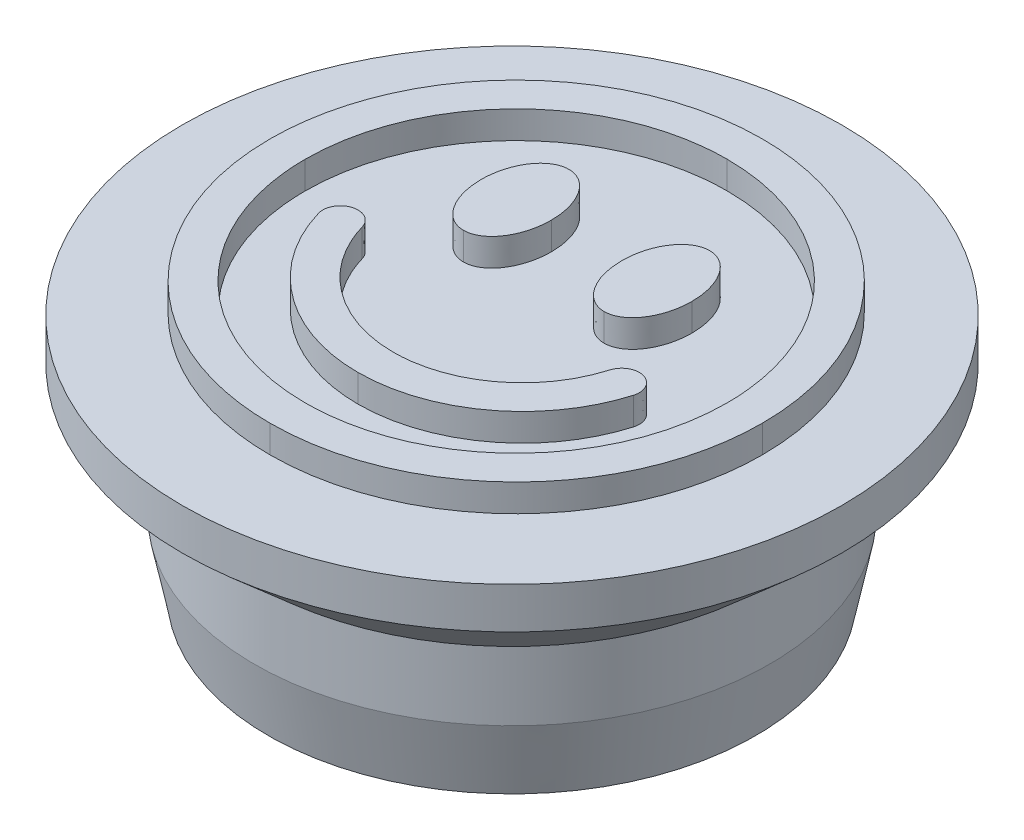
SolidWorks part; units mm, degrees
ref_plane "Front Plane" through (0, 0, 0) normal (0, 0, 1) x (1, 0, 0)
ref_plane "Top Plane" through (0, 0, 0) normal (0, 1, 0) x (1, 0, 0)
ref_plane "Right Plane" through (0, 0, 0) normal (1, 0, 0) x (0, 0, -1)
sketch "Sketch2" plane through (0, 0, 0) normal (0, 0, 1) x (1, 0, 0)
  line L0 (0, 0) -> (18.75, 0)
  line L1 (18.75, 0) -> (18.75, 10)
  line L2 (18.75, 10) -> (24, 14.6301)
  line L3 (24, 14.6301) -> (24, 17.6301)
  line L4 (24, 17.6301) -> (0, 17.6301)
  line L5 (0, 17.6301) -> (0, 0)
  dimension "D1" = 18.75
  dimension "D2" = 10
  dimension "D3" = 3
  dimension "D4" = 24
  dimension "D5" = 7
revolve "Revolve1" add sketch "Sketch2" angle 360 about L5
sketch "Sketch3" plane through (0, 17.6301, 0) normal (0, 1, 0) x (1, 0, 0)
  spline S0 degree 3 poles (0, 15.6649) (8.47, 15.6649) (15.36, 8.7749) (15.36, 0.3049) knots 0 0 0 0 1 1 1 1
  spline S1 degree 3 poles (15.36, 0.3049) (15.36, -8.1651) (8.47, -15.0551) (0, -15.0551) knots 0 0 0 0 1 1 1 1
  spline S2 degree 3 poles (0, -15.0551) (-8.47, -15.0551) (-15.36, -8.1651) (-15.36, 0.3049) knots 0 0 0 0 1 1 1 1
  spline S3 degree 3 poles (-15.36, 0.3049) (-15.36, 8.7749) (-8.47, 15.6649) (0, 15.6649) knots 0 0 0 0 1 1 1 1
  spline S4 degree 3 poles (0, 18.2249) (-9.8975, 18.2249) (-17.92, 10.2024) (-17.92, 0.3049) knots 0 0 0 0 1 1 1 1
  spline S5 degree 3 poles (-17.92, 0.3049) (-17.92, -9.5927) (-9.8975, -17.6151) (0, -17.6151) knots 0 0 0 0 1 1 1 1
  spline S6 degree 3 poles (0, -17.6151) (9.8975, -17.6151) (17.92, -9.5927) (17.92, 0.3049) knots 0 0 0 0 1 1 1 1
  spline S7 degree 3 poles (17.92, 0.3049) (17.92, 10.2024) (9.8975, 18.2249) (0, 18.2249) knots 0 0 0 0 1 1 1 1
  spline S8 degree 3 poles (-5.12, 9.2649) (-6.535, 9.2649) (-7.68, 7.5449) (-7.68, 5.4249) knots 0 0 0 0 1 1 1 1
  spline S9 degree 3 poles (-7.68, 5.4249) (-7.68, 3.3024) (-6.535, 1.5849) (-5.12, 1.5849) knots 0 0 0 0 1 1 1 1
  spline S10 degree 3 poles (-5.12, 1.5849) (-3.705, 1.5849) (-2.56, 3.3024) (-2.56, 5.4249) knots 0 0 0 0 1 1 1 1
  spline S11 degree 3 poles (-2.56, 5.4249) (-2.56, 7.5449) (-3.705, 9.2649) (-5.12, 9.2649) knots 0 0 0 0 1 1 1 1
  spline S12 degree 3 poles (5.12, 9.2649) (3.705, 9.2649) (2.56, 7.5449) (2.56, 5.4249) knots 0 0 0 0 1 1 1 1
  spline S13 degree 3 poles (2.56, 5.4249) (2.56, 3.3024) (3.705, 1.5849) (5.12, 1.5849) knots 0 0 0 0 1 1 1 1
  spline S14 degree 3 poles (5.12, 1.5849) (6.535, 1.5849) (7.68, 3.3024) (7.68, 5.4249) knots 0 0 0 0 1 1 1 1
  spline S15 degree 3 poles (7.68, 5.4249) (7.68, 7.5449) (6.535, 9.2649) (5.12, 9.2649) knots 0 0 0 0 1 1 1 1
  spline S16 degree 3 poles (11.47, -2.6127) (11.6675, -1.9351) (11.2775, -1.2251) (10.5975, -1.0251) knots 0 0 0 0 1 1 1 1
  spline S17 degree 3 poles (10.5975, -1.0251) (9.92, -0.8227) (9.21, -1.2202) (9.01, -1.8951) knots 0 0 0 0 1 1 1 1
  spline S18 degree 3 poles (9.01, -1.8951) (7.85, -5.8751) (4.145, -8.6551) (0, -8.6551) knots 0 0 0 0 1 1 1 1
  spline S19 degree 3 poles (0, -8.6551) (-4.145, -8.6551) (-7.85, -5.8751) (-9.0113, -1.8951) knots 0 0 0 0 1 1 1 1
  spline S20 degree 3 poles (-9.0113, -1.8951) (-9.2088, -1.2201) (-9.9113, -0.8227) (-10.5988, -1.0251) knots 0 0 0 0 1 1 1 1
  spline S21 degree 3 poles (-10.5988, -1.0251) (-11.2775, -1.2251) (-11.6663, -1.9351) (-11.4688, -2.6127) knots 0 0 0 0 1 1 1 1
  spline S22 degree 3 poles (-11.4688, -2.6127) (-9.9913, -7.6776) (-5.275, -11.2151) (0, -11.2151) knots 0 0 0 0 1 1 1 1
  spline S23 degree 3 poles (0, -11.2151) (5.275, -11.2151) (9.99, -7.6776) (11.47, -2.6127) knots 0 0 0 0 1 1 1 1
extrude "Boss-Extrude2" add sketch "Sketch3" along normal blind 2 contours S6 S7 S4 S5 S2 S3 S0 S1 | S14 S15 S12 S13 | S10 S11 S8 S9 | S23 S16 S17 S18 S19 S20 S21 S22
chamfer "Chamfer1" distance 1 distance2 5 1 edges at (-18.75, 0, 0)
